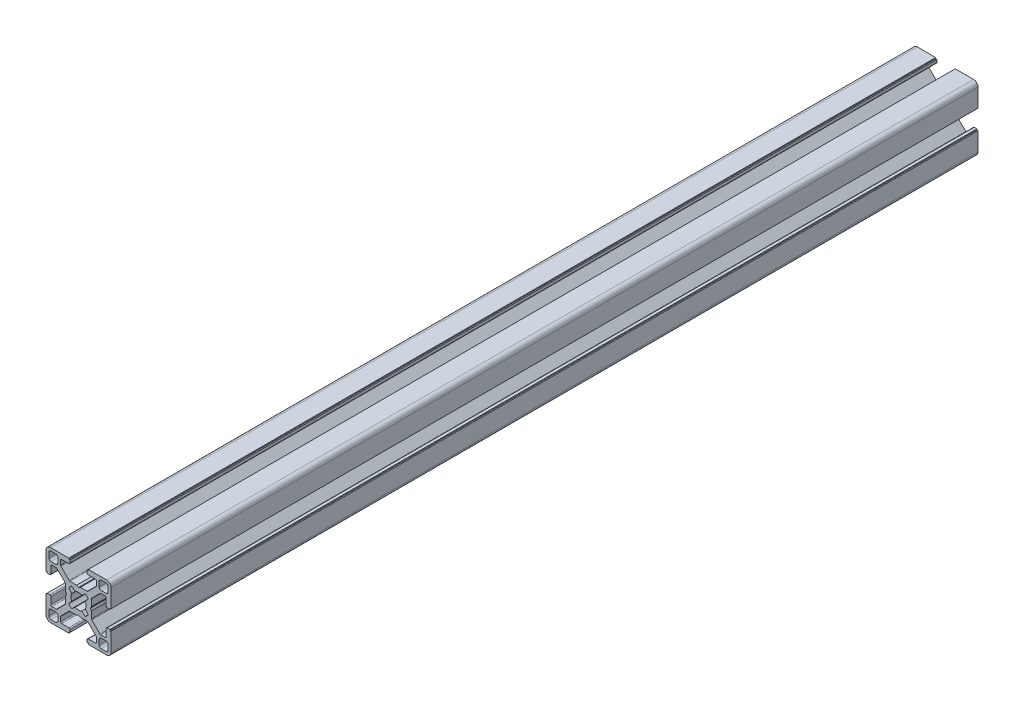
SolidWorks part; units mm, degrees
ref_plane "Front Plane" through (0, 0, 0) normal (0, 0, 1) x (1, 0, 0)
ref_plane "Top Plane" through (0, 0, 0) normal (0, 1, 0) x (1, 0, 0)
ref_plane "Right Plane" through (0, 0, 0) normal (1, 0, 0) x (0, 0, -1)
sketch "Sketch1" plane through (0, 0, 0) normal (0, 0, 1) x (1, 0, 0)
  line L0 (-15, 0) -> (15, 0) construction
  line L1 (0, -15) -> (0, 15) construction
  line L2 (-4.5, 15) -> (4.5, 15) construction
  line L3 (-4, -15) -> (4, -15) construction
  line L4 (-4.5, 15) -> (-4.5, 14.5)
  line L5 (-4.5, 14.5) -> (-4, 14.5)
  line L6 (-4, 14.5) -> (-4, 13.29)
  line L7 (-4.5, 12.79) -> (-7.7675, 12.79)
  line L8 (-8.2675, 12.29) -> (-8.2675, 10.2707)
  line L9 (-8.1211, 9.9171) -> (-4.3504, 6.1464)
  line L10 (-3.9968, 6) -> (0, 6)
  line L11 (0, 0) -> (-15, 15) construction
  line L12 (-4.5, 15) -> (-12.968, 15)
  line L14 (-12.705, 9.5135) -> (-10.5135, 9.5135)
  line L15 (-13.705, 10.5135) -> (-13.705, 12.705)
  line L16 (-12.705, 13.705) -> (-10.5135, 13.705)
  line L17 (-9.5135, 10.5135) -> (-9.5135, 12.705)
  line L18 (-13.705, 9.5135) -> (-9.5135, 13.705) construction
  line L19 (-13.705, 13.705) -> (-9.5135, 9.5135) construction
  line L20 (-3.1568, 4.5038) -> (-1.5303, 3.1477) construction
  line L21 (-4.5038, 3.1568) -> (-3.1477, 1.5303) construction
  line L22 (-6, 3.9968) -> (-6, 0)
  line L23 (-9.9171, 8.1211) -> (-6.1464, 4.3504)
  line L24 (-15, 4.5) -> (-15, 12.968)
  line L25 (-12.29, 8.2675) -> (-10.2707, 8.2675)
  line L26 (-12.79, 4.5) -> (-12.79, 7.7675)
  line L27 (-14.5, 4) -> (-13.29, 4)
  line L28 (-14.5, 4.5) -> (-14.5, 4)
  line L29 (-15, 4.5) -> (-14.5, 4.5)
  circle A0 centre (0, 0) radius 3.5
  arc A1 (-12.968, 15) -> (-15, 12.968) centre (-12.968, 12.968) ccw
  circle A2 centre (0, 0) radius 5.5 construction
  arc A3 (-10.5135, 9.5135) -> (-9.5135, 10.5135) centre (-10.5135, 10.5135) ccw
  arc A4 (-13.705, 12.705) -> (-12.705, 13.705) centre (-12.705, 12.705) cw
  arc A5 (-10.5135, 13.705) -> (-9.5135, 12.705) centre (-10.5135, 12.705) cw
  arc A6 (-12.705, 9.5135) -> (-13.705, 10.5135) centre (-12.705, 10.5135) cw
  arc A7 (-12.79, 4.5) -> (-13.29, 4) centre (-13.29, 4.5) cw
  arc A8 (-12.29, 8.2675) -> (-12.79, 7.7675) centre (-12.29, 7.7675) ccw
  arc A9 (-9.9171, 8.1211) -> (-10.2707, 8.2675) centre (-10.2707, 7.7675) ccw
  arc A10 (-6, 3.9968) -> (-6.1464, 4.3504) centre (-6.5, 3.9968) ccw
  arc A11 (-4.3504, 6.1464) -> (-3.9968, 6) centre (-3.9968, 6.5) ccw
  arc A12 (-4, 13.29) -> (-4.5, 12.79) centre (-4.5, 13.29) cw
  arc A13 (-7.7675, 12.79) -> (-8.2675, 12.29) centre (-7.7675, 12.29) ccw
  arc A14 (-8.2675, 10.2707) -> (-8.1211, 9.9171) centre (-7.7675, 10.2707) ccw
  point P4 (0, 0)
  point P8 (0, 0)
  point P13 (0, 15)
  point P15 (0, -15)
  point P16 (0, 6)
  point P23 (-11.6092, 11.6093)
  point P26 (0, 6)
  point P62 (-12.79, 4)
  point P65 (-12.79, 8.2675)
  point P68 (-10.0636, 8.2675)
  point P71 (-6, 4.2039)
  point P74 (-4.2039, 6)
  point P77 (-4, 12.79)
  point P80 (-8.2675, 12.79)
  point P83 (-8.2675, 10.0636)
  dimension "Center Hole Diameter" = 7
  dimension "D11" = 2.032
  dimension "D9" = 11
  dimension "D13" = 1
  dimension "D14" = 0.5
  dimension "Rail Height" = 30
  dimension "Rail Width" = 30
  dimension "T-Slot Width" = 8
  dimension "T-Slot Depth" = 9
  dimension "D1" = 9
  dimension "D2" = 45
  dimension "D3" = 8
  dimension "D4" = 2.21
  dimension "D5" = 16.535
  dimension "D7" = 2.54
  dimension "D6" = 1.295
  dimension "D8" = 1.246
  dimension "D10" = 10.36
  dimension "D12" = 1.905
sketch "Sketch2" plane through (0, 0, 0) normal (1, 0, 0) x (0, 0, -1)
  line L0 (-76.2, 0) -> (76.2, 0) construction
  line L2 (0, -15) -> (0, 15) construction
  line L3 (0, -15) -> (0, 15) construction
  line L4 (-76.2, -15) -> (-76.2, 15) construction
  line L5 (76.2, -15) -> (76.2, 15) construction
  point P0 (-38.7, 0)
  point P3 (0, 0)
  point P4 (38.7, 0)
  point P12 (-76.2, 0)
  point P14 (76.2, 0)
  dimension "Length" = 152.4
  dimension "D1" = 37.5
sketch "Sketch3" plane through (0, 0, 0) normal (0, 0, 1) x (1, 0, 0)
  line L0 (-4.5038, 3.1568) -> (-3.1477, 1.5303)
  line L1 (0, 3.5) -> (0, 5.5)
  line L2 (-5.5, 0) -> (-3.5, 0)
  line L7 (-6, 3.9968) -> (-6, 0) construction
  line L31 (-9.9171, 8.1211) -> (-6.1464, 4.3504) construction
  line L117 (-12.29, 8.2675) -> (-10.2707, 8.2675) construction
  line L118 (-12.79, 4.5) -> (-12.79, 7.7675) construction
  line L157 (-12.705, 9.5135) -> (-10.5135, 9.5135)
  line L158 (-9.5135, 10.5135) -> (-9.5135, 12.705)
  line L163 (-10.5135, 13.705) -> (-12.705, 13.705)
  line L164 (-13.705, 12.705) -> (-13.705, 10.5135)
  line L165 (-12.705, 9.5135) -> (-10.5135, 9.5135)
  line L166 (-9.5135, 10.5135) -> (-9.5135, 12.705)
  line L167 (-10.5135, 13.705) -> (-12.705, 13.705)
  line L168 (-13.705, 12.705) -> (-13.705, 10.5135)
  line L169 (-14.5, 4) -> (-13.29, 4) construction
  line L170 (-14.5, 4.5) -> (-14.5, 4) construction
  line L171 (-15, 4.5) -> (-14.5, 4.5) construction
  line L172 (-15, 4.5) -> (-15, 12.968) construction
  line L173 (-4.5, 15) -> (-12.968, 15) construction
  line L174 (-4.5, 15) -> (-4.5, 14.5) construction
  line L175 (-4.5, 14.5) -> (-4, 14.5) construction
  line L176 (-4, 14.5) -> (-4, 13.29) construction
  line L177 (-4.5, 12.79) -> (-7.7675, 12.79) construction
  line L178 (-8.2675, 12.29) -> (-8.2675, 10.2707) construction
  line L179 (-8.1211, 9.9171) -> (-4.3504, 6.1464) construction
  line L180 (-3.9968, 6) -> (0, 6) construction
  line L181 (-6, 3.9968) -> (-6, 0.866)
  line L182 (-9.9171, 8.1211) -> (-6.1464, 4.3504)
  line L183 (-12.29, 8.2675) -> (-10.2707, 8.2675)
  line L184 (-12.79, 4.5) -> (-12.79, 7.7675)
  line L185 (-14.5, 4) -> (-13.29, 4)
  line L186 (-14.5, 4.5) -> (-14.5, 4)
  line L187 (-15, 4.5) -> (-14.5, 4.5)
  line L188 (-15, 4.5) -> (-15, 12.968)
  line L189 (-4.5, 15) -> (-12.968, 15)
  line L190 (-4.5, 15) -> (-4.5, 14.5)
  line L191 (-4.5, 14.5) -> (-4, 14.5)
  line L192 (-4, 14.5) -> (-4, 13.29)
  line L193 (-4.5, 12.79) -> (-7.7675, 12.79)
  line L194 (-8.2675, 12.29) -> (-8.2675, 10.2707)
  line L195 (-8.1211, 9.9171) -> (-4.3504, 6.1464)
  line L196 (-3.9968, 6) -> (-0.866, 6)
  line L197 (-0.866, 6) -> (0, 5.5)
  line L198 (0, -15) -> (0, 15) construction
  line L199 (0, 0) -> (-15, 15) construction
  line L200 (0, 0) -> (-15, 15) construction
  line L201 (-3.1568, 4.5038) -> (-1.5303, 3.1477) construction
  line L202 (-3.1568, 4.5038) -> (-1.5303, 3.1477)
  line L203 (-6, 0.866) -> (-5.5, 0)
  line L204 (-15, 0) -> (15, 0) construction
  line L205 (-15, 0) -> (15, 0) construction
  line L206 (0, -15) -> (0, 15) construction
  arc A0 (-3.5, 0) -> (-3.1477, 1.5303) centre (0, 0) cw
  arc A10 (-6, 3.9968) -> (-6.1464, 4.3504) centre (-6.5, 3.9968) ccw construction
  circle A16 centre (0, 0) radius 3.5
  arc A18 (0, 3.5) -> (-1.5303, 3.1477) centre (0, 0) ccw
  arc A20 (-9.9171, 8.1211) -> (-10.2707, 8.2675) centre (-10.2707, 7.7675) ccw construction
  arc A22 (-12.29, 8.2675) -> (-12.79, 7.7675) centre (-12.29, 7.7675) ccw construction
  arc A28 (-13.29, 4) -> (-12.79, 4.5) centre (-13.29, 4.5) ccw construction
  arc A29 (-10.5135, 9.5135) -> (-9.5135, 10.5135) centre (-10.5135, 10.5135) ccw
  arc A30 (-9.5135, 12.705) -> (-10.5135, 13.705) centre (-10.5135, 12.705) ccw
  arc A31 (-12.705, 13.705) -> (-13.705, 12.705) centre (-12.705, 12.705) ccw
  arc A32 (-13.705, 10.5135) -> (-12.705, 9.5135) centre (-12.705, 10.5135) ccw
  arc A33 (-10.5135, 9.5135) -> (-9.5135, 10.5135) centre (-10.5135, 10.5135) ccw
  arc A34 (-9.5135, 12.705) -> (-10.5135, 13.705) centre (-10.5135, 12.705) ccw
  arc A35 (-12.705, 13.705) -> (-13.705, 12.705) centre (-12.705, 12.705) ccw
  arc A36 (-13.705, 10.5135) -> (-12.705, 9.5135) centre (-12.705, 10.5135) ccw
  arc A37 (-12.968, 15) -> (-15, 12.968) centre (-12.968, 12.968) ccw construction
  arc A38 (-4.5, 12.79) -> (-4, 13.29) centre (-4.5, 13.29) ccw construction
  arc A39 (-7.7675, 12.79) -> (-8.2675, 12.29) centre (-7.7675, 12.29) ccw construction
  arc A40 (-8.2675, 10.2707) -> (-8.1211, 9.9171) centre (-7.7675, 10.2707) ccw construction
  arc A41 (-4.3504, 6.1464) -> (-3.9968, 6) centre (-3.9968, 6.5) ccw construction
  arc A42 (-6, 3.9968) -> (-6.1464, 4.3504) centre (-6.5, 3.9968) ccw
  arc A43 (-9.9171, 8.1211) -> (-10.2707, 8.2675) centre (-10.2707, 7.7675) ccw
  arc A44 (-12.29, 8.2675) -> (-12.79, 7.7675) centre (-12.29, 7.7675) ccw
  arc A45 (-13.29, 4) -> (-12.79, 4.5) centre (-13.29, 4.5) ccw
  arc A46 (-12.968, 15) -> (-15, 12.968) centre (-12.968, 12.968) ccw
  arc A47 (-4.5, 12.79) -> (-4, 13.29) centre (-4.5, 13.29) ccw
  arc A48 (-7.7675, 12.79) -> (-8.2675, 12.29) centre (-7.7675, 12.29) ccw
  arc A49 (-8.2675, 10.2707) -> (-8.1211, 9.9171) centre (-7.7675, 10.2707) ccw
  arc A50 (-4.3504, 6.1464) -> (-3.9968, 6) centre (-3.9968, 6.5) ccw
  circle A51 centre (0, 0) radius 5.5 construction
  arc A52 (-3.1568, 4.5038) -> (-4.5038, 3.1568) centre (0, 0) ccw
  dimension "D3" = 60
  dimension "D4" = 60
  dimension "D1" = 0
  dimension "D2" = 0
extrude "Boss-Extrude1" add sketch "Sketch3" along normal mid plane 400
pattern_circular "CirPattern1" count 4 over 360 about axis through (0, 0, 0) along (0, 0, 1) of "Boss-Extrude1"
ref_plane "Contact Plane1" through (15, 0, 0) normal (1, 0, 0) x (0, 0, -1)
ref_plane "Contact Plane2" through (0, -15, 0) normal (0, 1, 0) x (1, 0, 0)
ref_plane "Contact Plane3" through (-15, 0, 0) normal (1, 0, 0) x (0, 0, -1)
ref_plane "Contact Plane4" through (0, 15, 0) normal (0, 1, 0) x (1, 0, 0)
equation "\"D1@Sketch2\" = \"Rail Height@Sketch1\" * 1.25"
equation "\"D1@Sketch1\"=\"T-Slot Width@Sketch1\"+1mm"
equation "\"D3@Sketch1\"= \"T-Slot Width@Sketch1\""
equation "\"D1@Boss-Extrude1\"=\"Length\""
equation "\"Length\"= 400"
